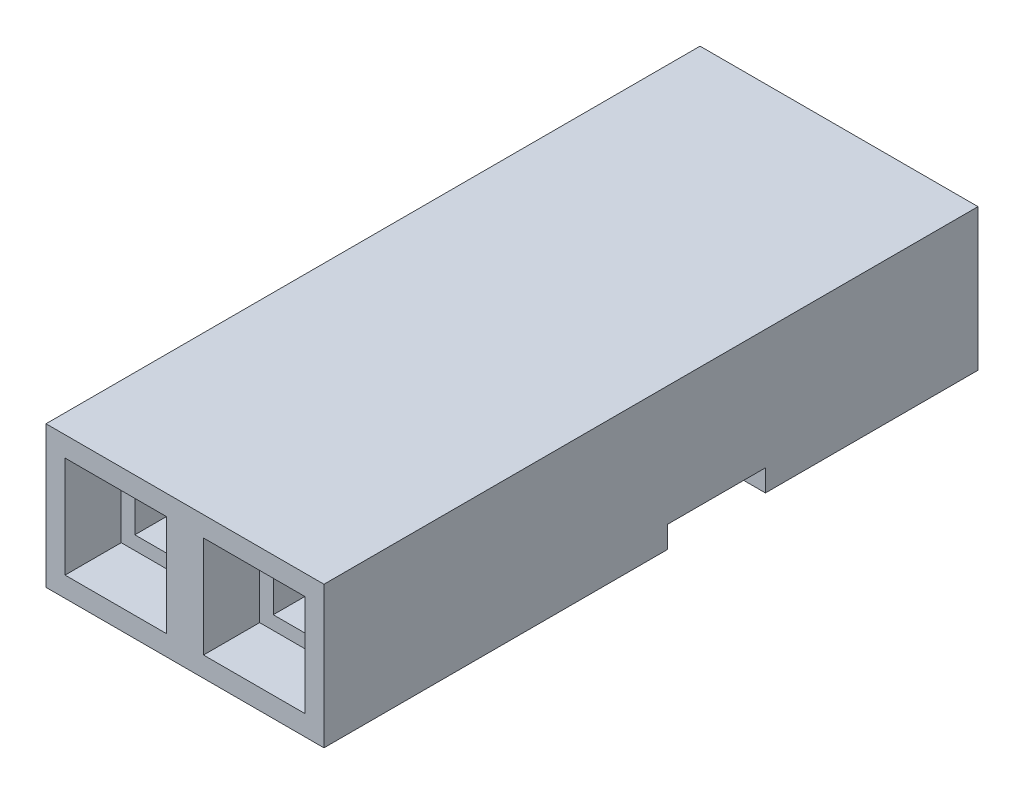
SolidWorks part; units mm, degrees
ref_plane "Front Plane" through (0, 0, 0) normal (0, 0, 1) x (1, 0, 0)
ref_plane "Top Plane" through (0, 0, 0) normal (0, 1, 0) x (1, 0, 0)
ref_plane "Right Plane" through (0, 0, 0) normal (1, 0, 0) x (0, 0, -1)
sketch "Sketch1" plane through (0, 0, 0) normal (0, 1, 0) x (1, 0, 0)
  line L0 (-2.55, 7) -> (-2.55, -7)
  line L1 (2.55, -7) -> (-2.55, -7)
  line L3 (2.55, 7) -> (-2.55, 7)
  line L5 (2.55, -7) -> (-2.55, 7) construction
  line L6 (2.55, 7) -> (-2.55, -7) construction
  line L9 (2.55, 7) -> (2.55, -7)
  line L10 (0, 0) -> (0, -7) construction
  point P0 (0, 0)
  dimension "D1" = 14
  dimension "D4" = 5.1
extrude "Boss-Extrude1" add sketch "Sketch1" along normal mid plane 2.6
sketch "Sketch2" plane through (0, 0, -7) normal (0, 0, -1) x (-1, 0, 0)
  line L0 (-1.27, 0) -> (1.27, 0) construction
  line L1 (-0.34, -0.93) -> (-2.2, -0.93)
  line L2 (-0.34, -0.93) -> (-0.34, 0.93)
  line L3 (-0.34, 0.93) -> (-2.2, 0.93)
  line L4 (-2.2, -0.93) -> (-2.2, 0.93)
  line L5 (-0.34, -0.93) -> (-2.2, 0.93) construction
  line L6 (-0.34, 0.93) -> (-2.2, -0.93) construction
  line L7 (2.2, -0.93) -> (0.34, -0.93)
  line L8 (2.2, -0.93) -> (2.2, 0.93)
  line L9 (2.2, 0.93) -> (0.34, 0.93)
  line L10 (0.34, -0.93) -> (0.34, 0.93)
  line L11 (2.2, -0.93) -> (0.34, 0.93) construction
  line L12 (2.2, 0.93) -> (0.34, -0.93) construction
  point P0 (-1.27, 0)
  point P5 (1.27, 0)
  point P12 (0, 0)
  dimension "D1" = 4.4
  dimension "D2" = 2.54
extrude "Cut-Extrude1" cut sketch "Sketch2" against normal through all
sketch "Sketch3" plane through (0, 0, 0) normal (1, 0, 0) x (0, 0, -1)
  line L0 (1.3, -1.3) -> (1.3, -0.9)
  line L2 (1.3, -0.9) -> (3.1, -0.9)
  line L3 (3.1, -0.9) -> (3.1, -1.3)
  line L6 (1.3, -1.3) -> (3.1, -1.3)
  line L7 (-7, -1.3) -> (7, -1.3) construction
  line L8 (-7, 1.3) -> (7, 1.3) construction
  line L9 (7, 1.3) -> (7, -1.3) construction
  dimension "D1" = 1.8
  dimension "D2" = 2.2
  dimension "D3" = 3.9
extrude "Cut-Extrude2" cut sketch "Sketch3" against normal through all and the other way through all
sketch "Sketch8" plane through (0, -1.3, 0) normal (0, -1, 0) x (1, 0, 0)
  line L0 (-2.55, -1.3) -> (2.55, -1.3) construction
  line L1 (-2.2, -1.3) -> (-2.1, -1.3)
  line L2 (-2.2, -1.3) -> (-2.2, 2)
  line L3 (-2.2, 2) -> (-2.1, 2)
  line L4 (-2.1, -1.3) -> (-2.1, 2)
  line L5 (-2.2, 7) -> (-2.2, -7) construction
  line L6 (-0.34, 7) -> (-0.34, -7) construction
  line L7 (-0.34, -1.3) -> (-0.44, -1.3)
  line L8 (-0.34, -1.3) -> (-0.34, 2)
  line L9 (-0.34, 2) -> (-0.44, 2)
  line L10 (-0.44, -1.3) -> (-0.44, 2)
  line L11 (2.2, 7) -> (2.2, -7) construction
  line L12 (0.34, -1.3) -> (0.44, -1.3)
  line L13 (0.34, -1.3) -> (0.34, 2)
  line L14 (0.34, 2) -> (0.44, 2)
  line L15 (0.44, -1.3) -> (0.44, 2)
  line L16 (2.2, -1.3) -> (2.1, -1.3)
  line L17 (2.2, -1.3) -> (2.2, 2)
  line L18 (2.2, 2) -> (2.1, 2)
  line L19 (2.1, -1.3) -> (2.1, 2)
  line L20 (-2.55, 7) -> (2.55, 7) construction
  dimension "D1" = 5
  dimension "D2" = 0.1
extrude "Cut-Extrude3" cut sketch "Sketch8" against normal up to next
sketch "Sketch5" plane through (0, 0, -7) normal (0, 0, -1) x (-1, 0, 0)
  line L0 (2.2, -0.93) -> (0.34, 0.93) construction
  line L1 (-0.82, -0.45) -> (-1.72, -0.45)
  line L2 (-0.82, -0.45) -> (-0.82, 0.45)
  line L3 (-0.82, 0.45) -> (-1.72, 0.45)
  line L4 (-1.72, -0.45) -> (-1.72, 0.45)
  line L5 (-0.82, -0.45) -> (-1.72, 0.45) construction
  line L6 (-0.82, 0.45) -> (-1.72, -0.45) construction
  line L7 (1.72, -0.45) -> (0.82, -0.45)
  line L8 (1.72, -0.45) -> (1.72, 0.45)
  line L9 (1.72, 0.45) -> (0.82, 0.45)
  line L10 (0.82, -0.45) -> (0.82, 0.45)
  line L11 (1.72, -0.45) -> (0.82, 0.45) construction
  line L12 (1.72, 0.45) -> (0.82, -0.45) construction
  line L32 (0.34, -0.93) -> (2.2, -0.93)
  line L33 (0.34, 0.93) -> (0.34, -0.93)
  line L34 (2.2, 0.93) -> (0.34, 0.93)
  line L35 (2.2, -0.93) -> (2.2, 0.93)
  line L36 (0.34, -0.93) -> (2.2, -0.93)
  line L37 (0.34, 0.93) -> (0.34, -0.93)
  line L38 (2.2, 0.93) -> (0.34, 0.93)
  line L39 (2.2, -0.93) -> (2.2, 0.93)
  line L40 (-2.2, -0.93) -> (-0.34, -0.93)
  line L41 (-2.2, 0.93) -> (-2.2, -0.93)
  line L42 (-0.34, 0.93) -> (-2.2, 0.93)
  line L43 (-0.34, -0.93) -> (-0.34, 0.93)
  line L44 (-2.2, -0.93) -> (-0.34, -0.93)
  line L45 (-2.2, 0.93) -> (-2.2, -0.93)
  line L46 (-0.34, 0.93) -> (-2.2, 0.93)
  line L47 (-0.34, -0.93) -> (-0.34, 0.93)
  point P0 (-1.27, 0)
  point P6 (1.27, 0)
  dimension "D1" = 0.9
  dimension "D3" = 0
  dimension "D4" = 0
extrude "Boss-Extrude2" add sketch "Sketch5" along normal up to surface (1 mm away) from offset 1 up to face at (-1.27, 0, -7) offset against normal yes
chamfer "Chamfer2" distance 0.5 angle 45 8 edges at (1.27, 0.45, -7) (1.72, 0, -7) (1.27, -0.45, -7) (0.82, 0, -7) (-0.82, 0, -7) (-1.27, -0.45, -7) (-1.72, 0, -7) (-1.27, 0.45, -7)
sketch "Sketch6" plane through (0, 0, -6) normal (0, 0, 1) x (1, 0, 0)
  line L7 (-2.2, -0.93) -> (-0.34, 0.93) construction
  line L8 (-0.37, -0.9) -> (-2.17, -0.9)
  line L9 (-0.37, -0.9) -> (-0.37, 0.9)
  line L10 (-0.37, 0.9) -> (-2.17, 0.9)
  line L11 (-2.17, -0.9) -> (-2.17, 0.9)
  line L12 (-0.37, -0.9) -> (-2.17, 0.9) construction
  line L13 (-0.37, 0.9) -> (-2.17, -0.9) construction
  line L14 (-2.2, 0.93) -> (-0.34, -0.93) construction
  line L15 (0.34, 0.93) -> (2.2, -0.93) construction
  line L16 (2.17, -0.9) -> (0.37, -0.9)
  line L17 (2.17, -0.9) -> (2.17, 0.9)
  line L18 (2.17, 0.9) -> (0.37, 0.9)
  line L19 (0.37, -0.9) -> (0.37, 0.9)
  line L20 (2.17, -0.9) -> (0.37, 0.9) construction
  line L21 (2.17, 0.9) -> (0.37, -0.9) construction
  line L26 (-0.62, 0.65) -> (-1.92, 0.65)
  line L27 (-1.92, -0.65) -> (-1.92, 0.65)
  line L28 (-0.62, -0.65) -> (-1.92, -0.65)
  line L29 (-0.62, -0.65) -> (-0.62, 0.65)
  line L30 (1.92, 0.65) -> (0.62, 0.65)
  line L31 (0.62, -0.65) -> (0.62, 0.65)
  line L32 (1.92, -0.65) -> (0.62, -0.65)
  line L33 (1.92, -0.65) -> (1.92, 0.65)
  point P8 (-1.27, 0)
  point P17 (1.27, 0)
  dimension "D1" = 1.8
  dimension "D2" = 0.25
extrude "Boss-Extrude3" add sketch "Sketch6" along normal blind 10 separate body
sketch "Sketch7" plane through (0, -0.9, 0) normal (0, -1, 0) x (1, 0, 0)
  line L1 (-0.44, -1.3) -> (-2.1, -1.3) construction
  line L6 (-2.17, 4) -> (-2.17, -6) construction
  line L7 (-2.17, -2.4) -> (-0.37, -2.4)
  line L8 (-2.17, -2.4) -> (-2.17, -1.4)
  line L9 (-2.17, -1.4) -> (-0.37, -1.4)
  line L10 (-0.37, -2.4) -> (-0.37, -1.4)
  line L11 (-0.37, 4) -> (-0.37, -6) construction
  line L12 (0.37, 4) -> (0.37, -6) construction
  line L13 (0.37, -2.4) -> (2.17, -2.4)
  line L14 (0.37, -2.4) -> (0.37, -1.4)
  line L15 (0.37, -1.4) -> (2.17, -1.4)
  line L16 (2.17, -2.4) -> (2.17, -1.4)
  line L17 (2.17, 4) -> (2.17, -6) construction
  dimension "D1" = 0.1
  dimension "D2" = 1
extrude "Boss-Extrude4" add sketch "Sketch7" along normal blind 0.1
sketch "Sketch9" plane through (0, 1.3, 0) normal (0, 1, 0) x (1, 0, 0)
  line L0 (2.55, 7) -> (-2.55, 7) construction
  line L1 (-2.55, -5) -> (2.55, -5)
  line L2 (-2.55, -5) -> (-2.55, -7)
  line L3 (-2.55, -7) -> (2.55, -7)
  line L4 (2.55, -5) -> (2.55, -7)
  line L5 (-2.55, 7) -> (-2.55, -7) construction
  dimension "D1" = 12
extrude "Cut-Extrude4" cut sketch "Sketch9" against normal through all
sketch "Sketch10" plane through (0, 0, -7) normal (0, 0, -1) x (-1, 0, 0)
  line L0 (-2.55, -1.3) -> (2.55, -1.3) construction
  line L1 (-1.72, -0.45) -> (-0.82, -0.45)
  line L2 (-1.72, -0.45) -> (-1.72, -1.3)
  line L3 (-1.72, -1.3) -> (-0.82, -1.3)
  line L4 (-0.82, -0.45) -> (-0.82, -1.3)
  line L5 (-0.82, -0.45) -> (-0.32, -0.95) construction
  line L6 (0.82, -0.45) -> (1.72, -0.45)
  line L7 (0.82, -0.45) -> (0.82, -1.3)
  line L8 (0.82, -1.3) -> (1.72, -1.3)
  line L9 (1.72, -0.45) -> (1.72, -1.3)
  line L10 (-1.72, -0.45) -> (-0.82, -0.45) construction
extrude "Cut-Extrude5" cut sketch "Sketch10" against normal blind 1
